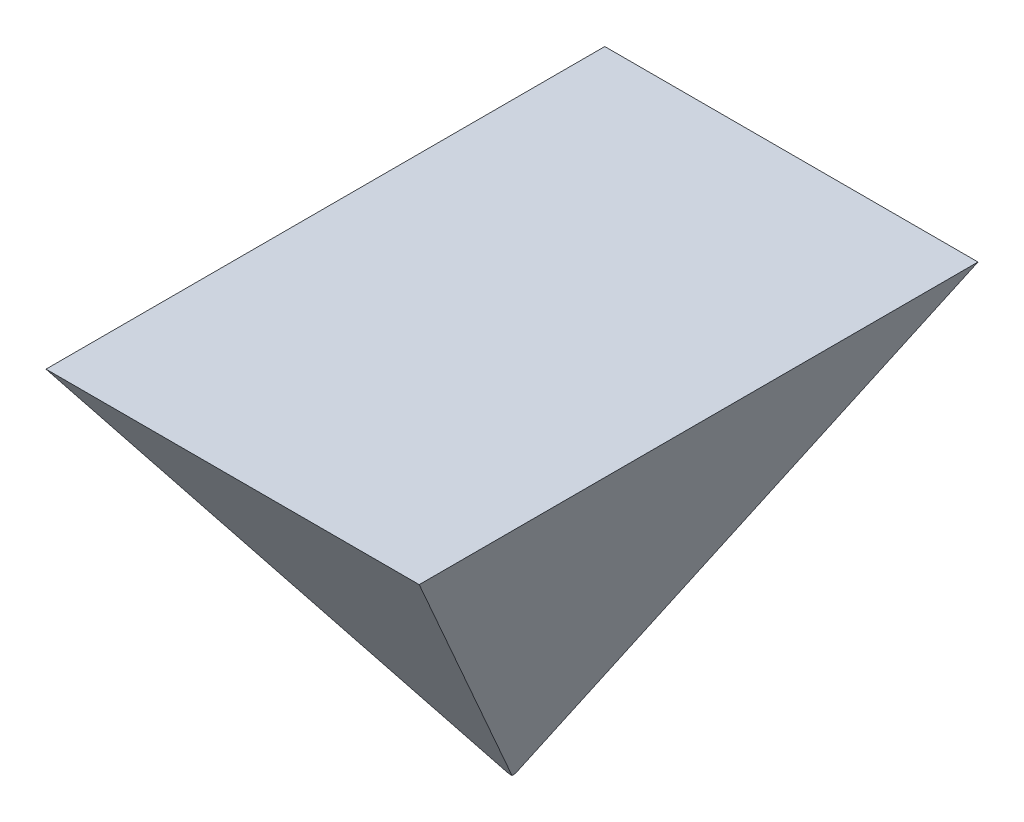
SolidWorks part; units mm, degrees
ref_plane "Front Plane" through (0, 0, 0) normal (0, 0, 1) x (1, 0, 0)
ref_plane "Top Plane" through (0, 0, 0) normal (0, 1, 0) x (1, 0, 0)
ref_plane "Right Plane" through (0, 0, 0) normal (1, 0, 0) x (0, 0, -1)
sketch "Sketch1" plane through (0, 0, 0) normal (0, 1, 0) x (1, 0, 0)
  line L5 (-2.5, -2.5) -> (2.5, -2.5)
  line L6 (-2.5, -2.5) -> (-2.5, 2.5)
  line L7 (-2.5, 2.5) -> (2.5, 2.5)
  line L8 (2.5, -2.5) -> (2.5, 2.5)
  line L9 (-2.5, -2.5) -> (2.5, 2.5) construction
  line L10 (-2.5, 2.5) -> (2.5, -2.5) construction
  point P0 (0, 0)
  dimension "D1" = 5
  dimension "D2" = 5
extrude "Boss-Extrude1" add sketch "Sketch1" along normal blind 600 draft 35
sketch "Sketch3" plane through (0, 0, 0) normal (0, 0, 1) x (1, 0, 0)
  line L0 (0, 0) -> (0, 736.3338) construction
  line L1 (-422.6245, 600) -> (-282.2846, 600)
  line L2 (-422.6245, 600) -> (-2.5, 0) construction
  line L3 (-422.6245, 600) -> (422.6245, 600) construction
  line L4 (-2.5, 0) -> (-282.2846, 600)
  line L5 (-2.5, 0) -> (2.5, 0) construction
  line L6 (-422.6245, 600) -> (-2.5, 0)
  line L7 (422.6245, 600) -> (2.5, 0)
  line L8 (422.6245, 600) -> (282.2846, 600)
  line L9 (2.5, 0) -> (282.2846, 600)
  point P8 (-4.2658, 0)
  dimension "D1" = 25
extrude "Cut-Extrude1" cut sketch "Sketch3" against normal through all both and the other way through all
